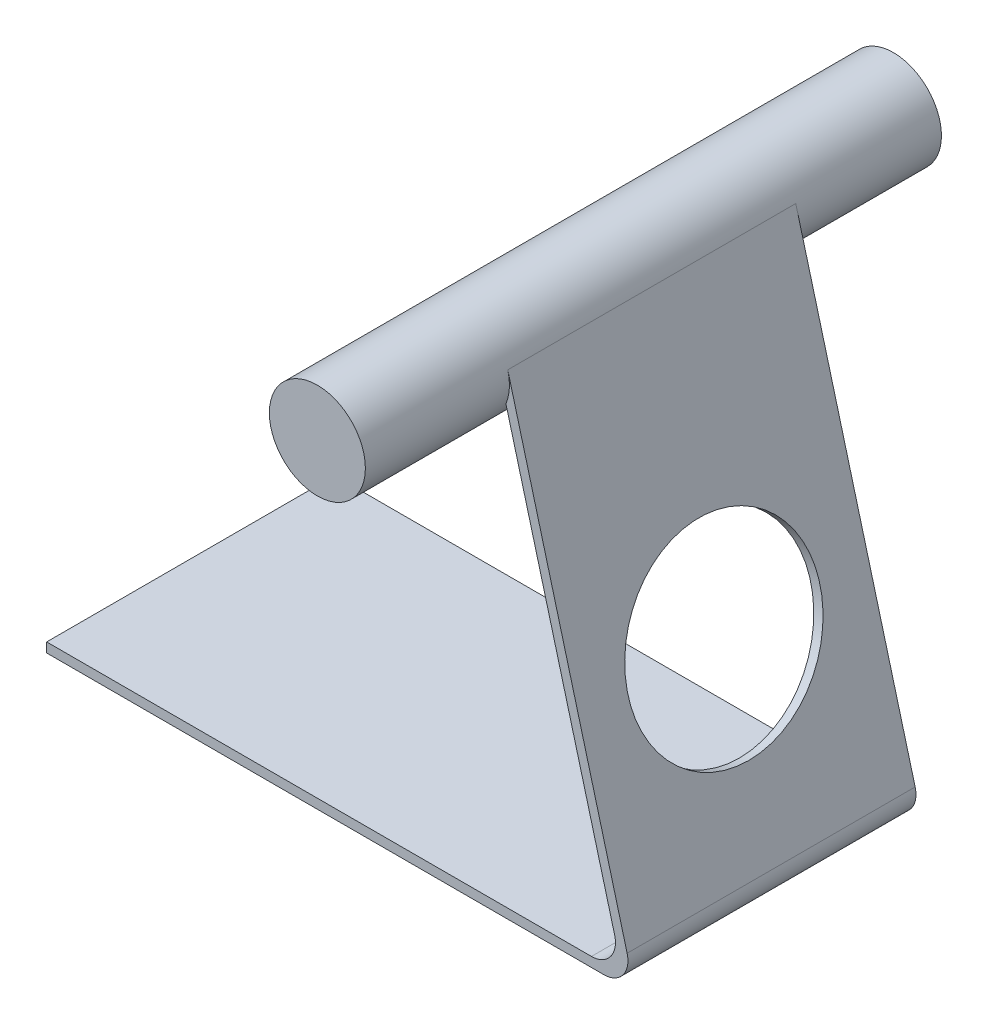
SolidWorks part; units mm, degrees
ref_plane "Front Plane" through (0, 0, 0) normal (0, 0, 1) x (1, 0, 0)
ref_plane "Top Plane" through (0, 0, 0) normal (0, 1, 0) x (1, 0, 0)
ref_plane "Right Plane" through (0, 0, 0) normal (1, 0, 0) x (0, 0, -1)
sketch "Sketch1" plane through (0, 0, 0) normal (0, 0, 1) x (1, 0, 0)
  line L0 (0, 0) -> (-152.4, 0)
  line L1 (0, 0) -> (-32.87, 122.6726)
  line L2 (-152.4, 0) -> (-152.4, -2.54)
  line L3 (-152.4, -2.54) -> (0, -2.54)
  line L4 (0, -2.54) -> (0, 0)
  line L5 (-32.87, 122.6726) -> (-30.4166, 123.33)
  line L6 (-30.4166, 123.33) -> (2.4535, 0.6574)
  line L7 (2.4535, 0.6574) -> (0, 0)
  line L8 (-30.4166, 123.33) -> (-42.6838, 120.043) construction
  line L9 (0, -2.54) -> (3.3102, -2.54)
  line L10 (2.4535, 0.6574) -> (3.3102, -2.54)
  circle A1 centre (-42.6838, 120.043) radius 12.7
  dimension "D9" = 90
  dimension "D1" = 127
  dimension "D2" = 152.4
  dimension "D3" = 75
  dimension "D4" = 90
  dimension "D5" = 2.54
  dimension "D6" = 90
  dimension "D7" = 2.54
  dimension "D8" = 12.7
  dimension "D10" = 180
extrude "Boss-Extrude1" add sketch "Sketch1" along normal blind 76.2
fillet "Fillet1" radius 6.35 1 edges at (0, 0, 38.1)
fillet "Fillet2" radius 6.35 1 edges at (3.3102, -2.54, 38.1)
sketch "Sketch2" plane through (2.4535, 0.6574, 0) normal (0.9659, 0.2588, 0) x (0, 0, -1)
  line L0 (-76.2, 65.9826) -> (0, 65.9826) construction
  line L1 (-76.2, 127) -> (-76.2, 4.9653) construction
  line L2 (0, 127) -> (0, 4.9653) construction
  circle A0 centre (-38.1, 53.2826) radius 25.4
  point P6 (-38.1, 53.2826)
  point P7 (-38.1, 65.9826)
  dimension "D2" = 50.8
  dimension "D1" = 12.7
extrude "Cut-Extrude1" cut sketch "Sketch2" against normal up to next and the other way through all
sketch "Sketch5" plane through (0, 0, 0) normal (0, 0, -1) x (-1, 0, 0)
  circle A0 centre (42.6838, 120.043) radius 12.7
extrude "Boss-Extrude4" add sketch "Sketch5" along normal blind 38.1
sketch "Sketch6" plane through (0, 0, 76.2) normal (0, 0, 1) x (1, 0, 0)
  circle A0 centre (-42.6838, 120.043) radius 12.7
extrude "Boss-Extrude5" add sketch "Sketch6" along normal blind 38.1
